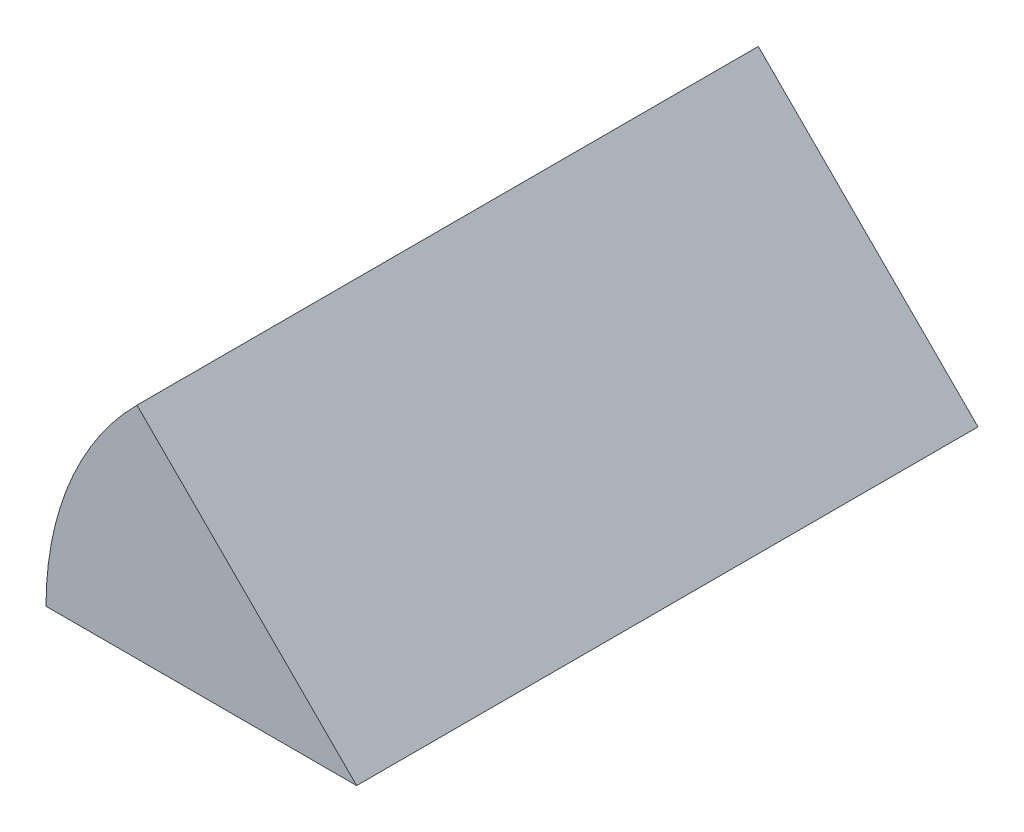
SolidWorks part; units mm, degrees
ref_plane "Alzado" through (0, 0, 0) normal (0, 0, 1) x (1, 0, 0)
ref_plane "Planta" through (0, 0, 0) normal (0, 1, 0) x (1, 0, 0)
ref_plane "Vista lateral" through (0, 0, 0) normal (1, 0, 0) x (0, 0, -1)
sketch "Croquis1" plane through (0, 0, 0) normal (0, 0, 1) x (1, 0, 0)
  line L1 (-25, 0) -> (0, 0)
  line L2 (0, 0) -> (-17.6777, 17.6777)
  arc A0 (-17.6777, 17.6777) -> (-25, 0) centre (0, 0) ccw
  dimension "D2" = 50
  dimension "D1" = 45
extrude "Saliente-Extruir1" add sketch "Croquis1" along normal blind 50
sketch "Croquis2" plane through (0, 0, 0) normal (0, 0, -1) x (-1, 0, 0)
  circle A0 centre (16.4977, 6.4725) radius 5
  dimension "D1" = 10
extrude "Cortar-Extruir1" cut sketch "Croquis2" against normal blind 10
